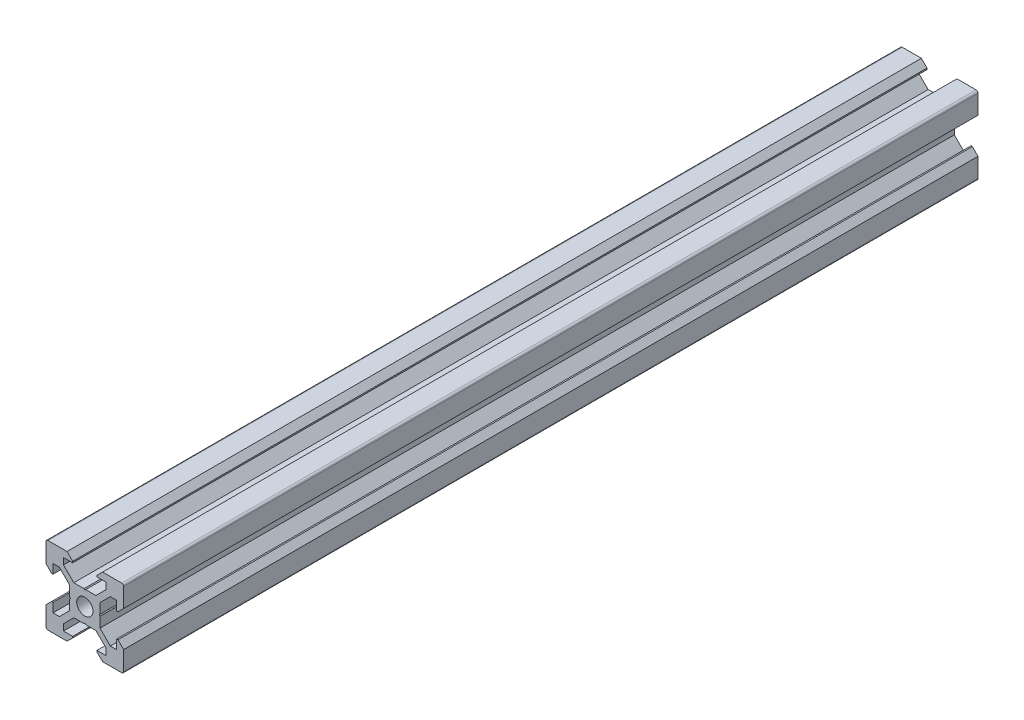
SolidWorks part; units mm, degrees
material "Aluminium"
ref_plane "Front Plane" through (0, 0, 0) normal (0, 0, 1) x (1, 0, 0)
ref_plane "Top Plane" through (0, 0, 0) normal (0, 1, 0) x (1, 0, 0)
ref_plane "Right Plane" through (0, 0, 0) normal (1, 0, 0) x (0, 0, -1)
sketch "Sketch1" plane through (0, 0, 0) normal (0, 0, 1) x (1, 0, 0)
  line L1 (9.5, -10) -> (-9.5, -10)
  line L2 (10, -9.5) -> (10, 9.5)
  line L3 (9.5, 10) -> (-9.5, 10)
  line L4 (-10, -9.5) -> (-10, 9.5)
  line L5 (10, -10) -> (-10, 10) construction
  line L6 (10, 10) -> (-10, -10) construction
  circle A0 centre (0, 0) radius 2.1
  arc A1 (-9.5, 10) -> (-10, 9.5) centre (-9.5, 9.5) ccw
  arc A2 (10, 9.5) -> (9.5, 10) centre (9.5, 9.5) ccw
  arc A3 (9.5, -10) -> (10, -9.5) centre (9.5, -9.5) ccw
  arc A4 (-9.5, -10) -> (-10, -9.5) centre (-9.5, -9.5) cw
  point P0 (0, 0)
  line B0 (0, 0) -> (0, 10) construction
  line B1 (0, 3.69) -> (-0.21, 3.9)
  line B2 (-0.21, 3.9) -> (-2.8393, 3.9)
  line B3 (-2.8393, 3.9) -> (-5.5, 6.5607)
  line B4 (-5.5, 6.5607) -> (-5.5, 8.2)
  line B5 (-5.5, 8.2) -> (-3.125, 8.2)
  line B6 (-3.125, 8.2) -> (-3.125, 8.545)
  line B7 (-3.125, 8.545) -> (-4.58, 10)
  line B8 (-4.58, 10) -> (4.58, 10)
  line B9 (0, 0) -> (-5.9132, 5.9132) construction
  line B10 (3.125, 8.545) -> (4.58, 10)
  line B11 (3.125, 8.2) -> (3.125, 8.545)
  line B12 (5.5, 8.2) -> (3.125, 8.2)
  line B13 (5.5, 6.5607) -> (5.5, 8.2)
  line B14 (2.8393, 3.9) -> (5.5, 6.5607)
  line B15 (0.21, 3.9) -> (2.8393, 3.9)
  line B16 (0, 3.69) -> (0.21, 3.9)
  line B17 (0, 0) -> (-10, 0) construction
  line B18 (-3.69, 0) -> (-3.9, -0.21)
  line B19 (-3.9, -0.21) -> (-3.9, -2.8393)
  line B20 (-3.9, -2.8393) -> (-6.5607, -5.5)
  line B21 (-6.5607, -5.5) -> (-8.2, -5.5)
  line B22 (-8.2, -5.5) -> (-8.2, -3.125)
  line B23 (-8.2, -3.125) -> (-8.545, -3.125)
  line B24 (-8.545, -3.125) -> (-10, -4.58)
  line B25 (-10, -4.58) -> (-10, 4.58)
  line B26 (0, 0) -> (-5.9132, -5.9132) construction
  line B27 (-8.545, 3.125) -> (-10, 4.58)
  line B28 (-8.2, 3.125) -> (-8.545, 3.125)
  line B29 (-8.2, 5.5) -> (-8.2, 3.125)
  line B30 (-6.5607, 5.5) -> (-8.2, 5.5)
  line B31 (-3.9, 2.8393) -> (-6.5607, 5.5)
  line B32 (-3.9, 0.21) -> (-3.9, 2.8393)
  line B33 (-3.69, 0) -> (-3.9, 0.21)
  line B34 (0, 0) -> (0, -10) construction
  line B35 (0, -3.69) -> (0.21, -3.9)
  line B36 (0.21, -3.9) -> (2.8393, -3.9)
  line B37 (2.8393, -3.9) -> (5.5, -6.5607)
  line B38 (5.5, -6.5607) -> (5.5, -8.2)
  line B39 (5.5, -8.2) -> (3.125, -8.2)
  line B40 (3.125, -8.2) -> (3.125, -8.545)
  line B41 (3.125, -8.545) -> (4.58, -10)
  line B42 (4.58, -10) -> (-4.58, -10)
  line B43 (0, 0) -> (5.9132, -5.9132) construction
  line B44 (-3.125, -8.545) -> (-4.58, -10)
  line B45 (-3.125, -8.2) -> (-3.125, -8.545)
  line B46 (-5.5, -8.2) -> (-3.125, -8.2)
  line B47 (-5.5, -6.5607) -> (-5.5, -8.2)
  line B48 (-2.8393, -3.9) -> (-5.5, -6.5607)
  line B49 (-0.21, -3.9) -> (-2.8393, -3.9)
  line B50 (0, -3.69) -> (-0.21, -3.9)
  line B51 (0, 0) -> (10, 0) construction
  line B52 (3.69, 0) -> (3.9, 0.21)
  line B53 (3.9, 0.21) -> (3.9, 2.8393)
  line B54 (3.9, 2.8393) -> (6.5607, 5.5)
  line B55 (6.5607, 5.5) -> (8.2, 5.5)
  line B56 (8.2, 5.5) -> (8.2, 3.125)
  line B57 (8.2, 3.125) -> (8.545, 3.125)
  line B58 (8.545, 3.125) -> (10, 4.58)
  line B59 (10, 4.58) -> (10, -4.58)
  line B60 (0, 0) -> (5.9132, 5.9132) construction
  line B61 (8.545, -3.125) -> (10, -4.58)
  line B62 (8.2, -3.125) -> (8.545, -3.125)
  line B63 (8.2, -5.5) -> (8.2, -3.125)
  line B64 (6.5607, -5.5) -> (8.2, -5.5)
  line B65 (3.9, -2.8393) -> (6.5607, -5.5)
  line B66 (3.9, -0.21) -> (3.9, -2.8393)
  line B67 (3.69, 0) -> (3.9, -0.21)
sketch_block_instance "V Slot 1-4"
sketch_block "V Slot 1" parameters "D1"=10, "D2"=11, "D3"=4.3, "D4"=1.8, "D5"=0.21, "D6"=45, "D7"=9.16, "D8"=1.5, "D9"=6.25
sketch_block_instance "V Slot 1-5"
sketch_block_instance "V Slot 1-6"
sketch_block_instance "V Slot 1-7" parameters "D1"=31.2546, "D3"=0.5, "D2"=9.6469
extrude "Boss-Extrude1" add sketch "Sketch1" along normal mid plane 220 contours B67 B52 B53 B54 B55 B56 B57 B58 L2 A2 L3 B10 B11 B12 B13 B14 B15 B16 B1 B2 B3 B4 B5 B6 B7 A1 L4 B27 B28 B29 B30 B31 B32 B33 B18 B19 B20 B21 B22 B23 B24 A4 L1 B44 B45 B46 B47 B48 B49
